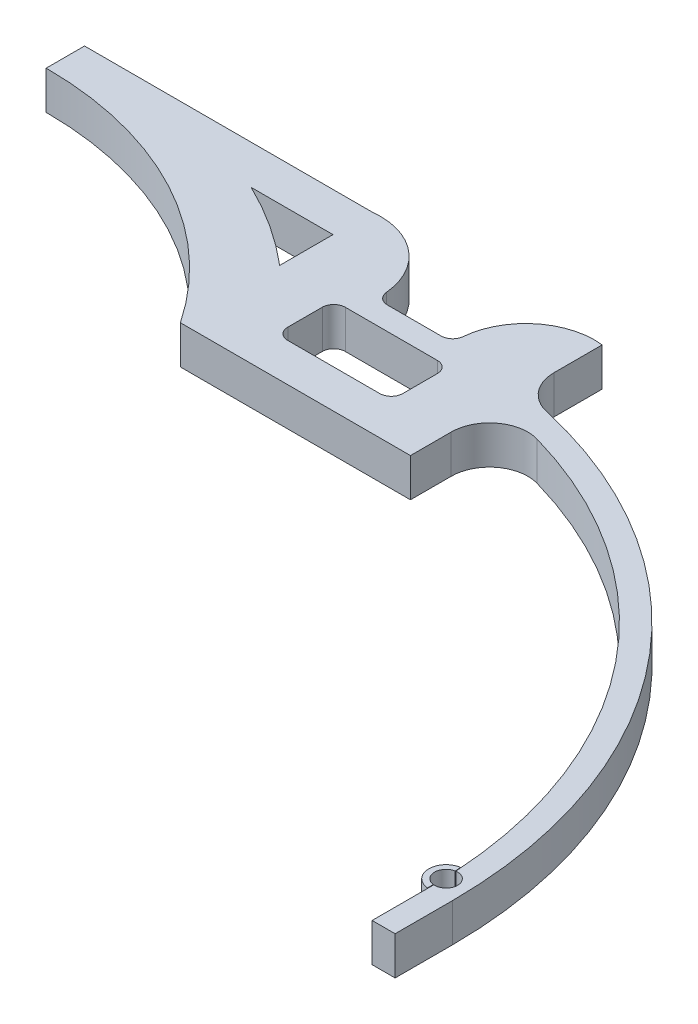
SolidWorks part; units mm, degrees
ref_plane "Front Plane" through (0, 0, 0) normal (0, 0, 1) x (1, 0, 0)
ref_plane "Top Plane" through (0, 0, 0) normal (0, 1, 0) x (1, 0, 0)
ref_plane "Right Plane" through (0, 0, 0) normal (1, 0, 0) x (0, 0, -1)
sketch "Sketch1" plane through (0, 0, 0) normal (0, 1, 0) x (1, 0, 0)
  line L0 (0, 0.2006) -> (0, 95.2006) construction
  line L1 (0, 126.2006) -> (0, 156.0407) construction
  line L2 (0, 105.2006) -> (0, 120.2006) construction
  line L3 (-15, 108.2006) -> (-15, 117.2006)
  line L5 (0, 0.2006) -> (129.9998, 0.2006) construction
  line L6 (30, 145.2006) -> (30, 132.6499)
  line L7 (30, 95.2006) -> (-30, 95.2006)
  line L8 (-12, 105.2006) -> (12, 105.2006)
  line L9 (15, 108.2006) -> (15, 117.2006)
  line L10 (12, 120.2006) -> (-12, 120.2006)
  line L11 (-7.012, 126.2006) -> (7.012, 126.2006)
  line L12 (-105, 145.2006) -> (-30, 145.2006)
  line L13 (-105, 145.2006) -> (-105, 135.2006)
  line L14 (-51.3394, 135) -> (-30, 135)
  line L15 (-30, 135) -> (-30, 121.0917)
  line L16 (135.9998, 0.2006) -> (135.9998, -14.7994)
  line L17 (135.9998, -14.7994) -> (129.9998, -14.7994)
  line L18 (129.9998, 0.2006) -> (129.9998, -14.7994)
  line L19 (30, 105.8301) -> (30, 95.2006)
  arc A0 (10, 128.932) -> (30, 145.2006) centre (27.9277, 127.3203) cw
  arc A1 (12, 105.2006) -> (15, 108.2006) centre (12, 108.2006) ccw
  arc A2 (15, 117.2006) -> (12, 120.2006) centre (12, 117.2006) ccw
  arc A3 (7.012, 126.2006) -> (10, 128.932) centre (7.012, 129.2006) ccw
  arc A4 (-7.012, 126.2006) -> (-10, 128.932) centre (-7.012, 129.2006) cw
  arc A5 (-15, 117.2006) -> (-12, 120.2006) centre (-12, 117.2006) cw
  arc A6 (-12, 105.2006) -> (-15, 108.2006) centre (-12, 108.2006) cw
  arc A7 (-10, 128.932) -> (-30, 145.2006) centre (-27.9277, 127.3203) ccw
  arc A8 (-105, 135.2006) -> (-30, 95.2006) centre (-105, 44.8881) cw
  arc A9 (-51.3394, 135) -> (-30, 121.0917) centre (-95, 44.6875) cw
  arc A10 (37.7941, 122.8962) -> (135.9998, 0.2006) centre (10, 0) cw
  arc A11 (37.7941, 122.8962) -> (30, 132.6499) centre (40, 132.6499) cw
  arc A12 (42.7273, 115.451) -> (129.9998, 0.2006) centre (10, 0) cw
  arc A13 (42.7273, 115.451) -> (30, 105.8301) centre (40, 105.8301) ccw
  point P15 (0, 106.3628)
  point P20 (0, 98.102)
  dimension "D5" = 3
  dimension "D9" = 18
  dimension "D10" = 10
  dimension "D14" = 6
  dimension "D1" = 10
  dimension "D2" = 15
  dimension "D3" = 30
  dimension "D4" = 50
  dimension "D6" = 75
  dimension "D7" = 15
  dimension "D8" = 6
  dimension "D11" = 95
  dimension "D12" = 15
  dimension "D13" = 10
  dimension "D15" = 20
extrude "Boss-Extrude1" add sketch "Sketch1" along normal mid plane 10
sketch "Sketch3" plane through (0, 5, 0) normal (0, 1, 0) x (1, 0, 0)
  arc A0 (129.5603, 8.7247) -> (129.8781, -0.2129) centre (130.2233, 4.2738) ccw
  arc A1 (129.8781, -0.2129) -> (129.5603, 8.7247) centre (9.8782, -0.0043) ccw
  dimension "D1" = 9
extrude "Boss-Extrude2" add sketch "Sketch3" against normal blind 10 separate body
sketch "Sketch4" plane through (0, 5, 0) normal (0, 1, 0) x (1, 0, 0)
  circle A0 centre (130.2233, 4.2738) radius 3
extrude "Cut-Extrude2" cut sketch "Sketch4" against normal blind 7
